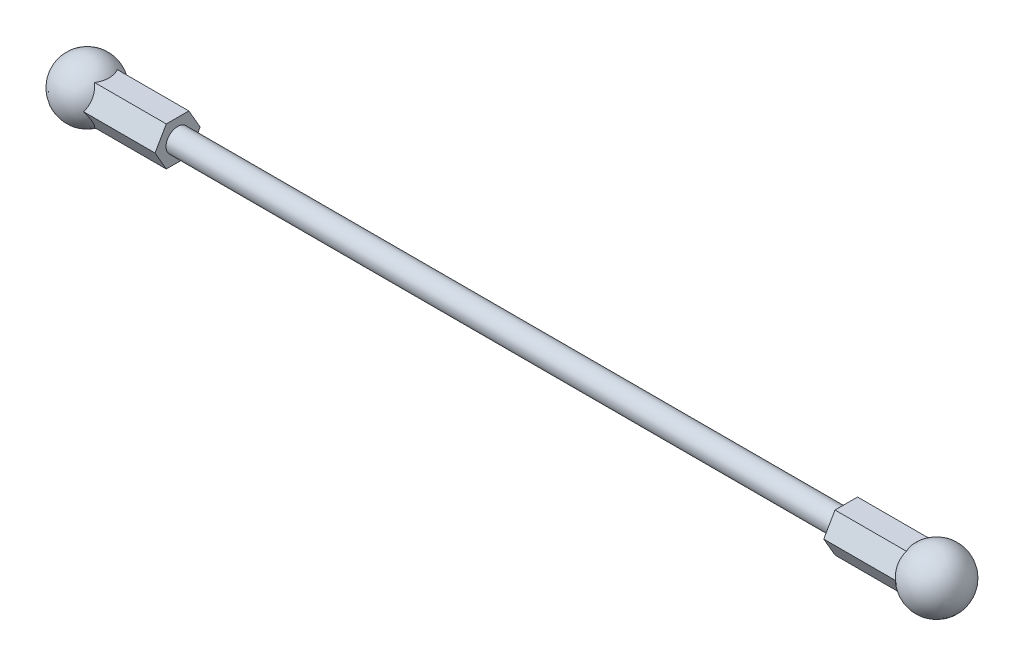
SolidWorks part; units mm, degrees
ref_plane "Front Plane" through (0, 0, 0) normal (0, 0, 1) x (1, 0, 0)
ref_plane "Top Plane" through (0, 0, 0) normal (0, 1, 0) x (1, 0, 0)
ref_plane "Right Plane" through (0, 0, 0) normal (1, 0, 0) x (0, 0, -1)
sketch "Sketch2" plane through (0, 0, 0) normal (0, 0, 1) x (1, 0, 0)
  line L5 (0, 3) -> (0, -3)
  arc A0 (0, 3) -> (0, -3) centre (0, 0) cw
  dimension "D3" = 3
revolve "Revolve1" add sketch "Sketch2" angle 360 about L5
ref_point "Point1"
ref_plane "Plane3" through (87, 0, 0) normal (1, 0, 0) x (0, 0, -1)
sketch "Sketch7" plane through (87, 0, 0) normal (1, 0, 0) x (0, 0, -1)
  line L0 (0, 3) -> (0, -3)
  circle A0 centre (0, 0) radius 3 construction
  arc A1 (0, 3) -> (0, -3) centre (0, 0) cw
revolve "Revolve2" add sketch "Sketch7" angle 360 about L0
ref_point "Point2"
sketch "Sketch3" plane through (0, 0, 0) normal (1, 0, 0) x (0, 0, -1)
  line L1 (1.1547, -2) -> (2.3094, 0)
  line L2 (2.3094, 0) -> (1.1547, 2)
  line L3 (1.1547, 2) -> (-1.1547, 2)
  line L4 (-1.1547, 2) -> (-2.3094, 0)
  line L5 (-2.3094, 0) -> (-1.1547, -2)
  line L6 (-1.1547, -2) -> (1.1547, -2)
  circle A0 centre (0, 0) radius 2 construction
  dimension "D1" = 4
extrude "Boss-Extrude2" add sketch "Sketch3" along normal blind 9.25 contours L4 L5 L6 L1 L2 L3
ref_plane "Plane4" through (43.5, 0, 0) normal (1, 0, 0) x (0, 0, -1)
mirror "Mirror3" about plane through (43.5, 0, 0) normal (1, 0, 0) of "Boss-Extrude2"
sketch "Sketch5" plane through (9.25, 0, 0) normal (1, 0, 0) x (0, 0, -1)
  line L0 (-2.3094, 0) -> (-1.1827, 0) construction
  circle A0 centre (0.0079, 0) radius 1.1906
  dimension "D1" = 2.3813
extrude "Boss-Extrude3" add sketch "Sketch5" along normal up to surface (68.5 mm away) up to face at (77.75, 0, 0)
